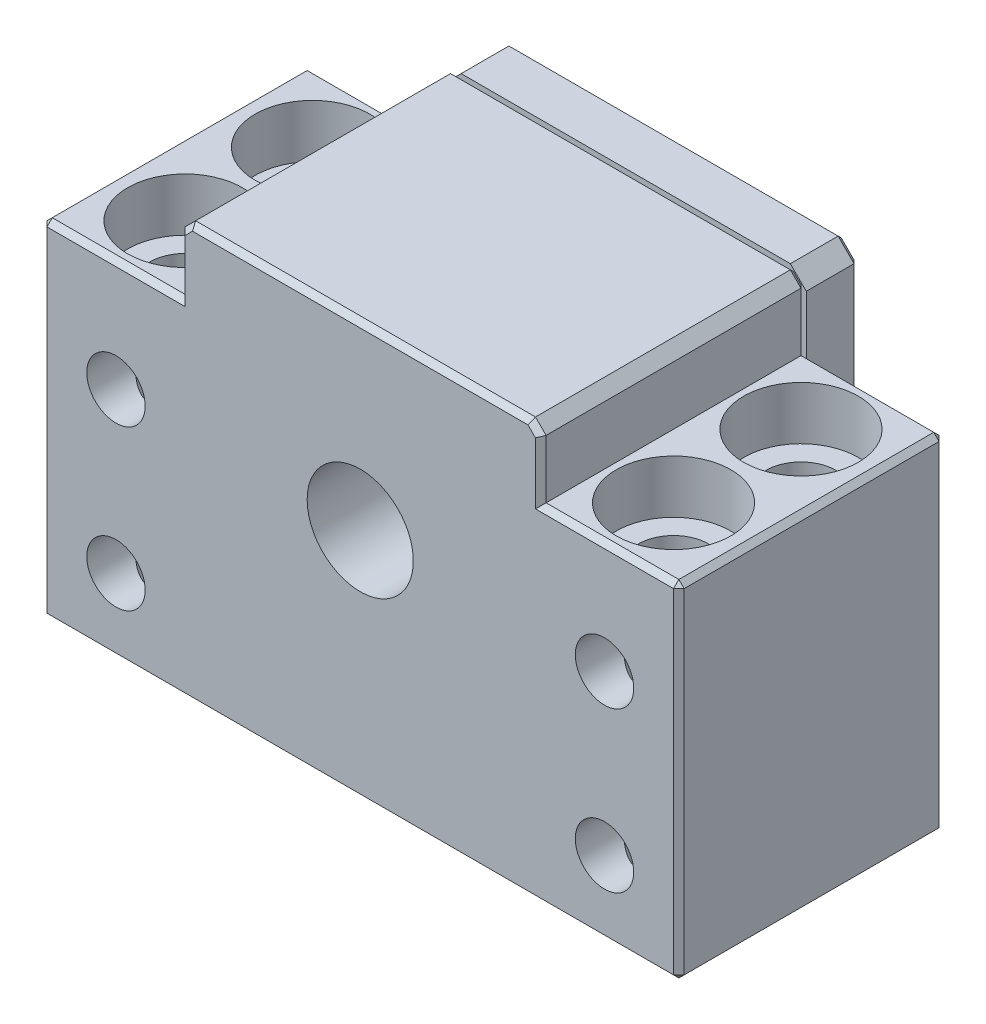
SolidWorks part; units mm, degrees
ref_plane "前视基准面" through (0, 0, 0) normal (0, 0, 1) x (1, 0, 0)
ref_plane "上视基准面" through (0, 0, 0) normal (0, 1, 0) x (1, 0, 0)
ref_plane "右视基准面" through (0, 0, 0) normal (1, 0, 0) x (0, 0, -1)
sketch "草图1" plane through (0, 0, 0) normal (0, 1, 0) x (1, 0, 0)
  line L0 (-23, 12.5) -> (-23, -12.5) construction
  line L1 (-30, 12.5) -> (30, 12.5)
  line L2 (-30, 12.5) -> (-30, -12.5)
  line L3 (-30, -12.5) -> (30, -12.5)
  line L4 (30, 12.5) -> (30, -12.5)
  line L5 (23, 12.5) -> (23, -12.5) construction
  line L6 (-30, -6) -> (30, -6) construction
  line L7 (30, 6) -> (-30, 6) construction
  circle A0 centre (23, 6) radius 3.3
  circle A1 centre (23, -6) radius 3.3
  circle A2 centre (-23, 6) radius 3.3
  circle A3 centre (-23, -6) radius 3.3
  point P0 (0, 0)
  dimension "D1" = 60
  dimension "D2" = 25
  dimension "D3" = 7
  dimension "D4" = 7
  dimension "D5" = 6
  dimension "D6" = 6
extrude "凸台-拉伸1" add sketch "草图1" along normal blind 32.5
sketch "草图2" plane through (0, 32.5, 0) normal (0, 1, 0) x (1, 0, 0)
  circle A0 centre (-23, -6) radius 5.4
  circle A1 centre (-23, 6) radius 5.4
  circle A2 centre (23, -6) radius 5.4
  circle A3 centre (23, 6) radius 5.4
extrude "切除-拉伸1" cut sketch "草图2" against normal blind 5
sketch "草图3" plane through (0, 0, 12.5) normal (0, 0, 1) x (1, 0, 0)
  line L0 (-30, 22) -> (30, 22) construction
  line L1 (-30, 32.5) -> (-30, 0) construction
  line L2 (30, 32.5) -> (30, 0) construction
  line L3 (-30, 7) -> (30, 7) construction
  line L4 (-30, 0) -> (30, 0) construction
  line L5 (23, 0) -> (23, 32.5) construction
  line L6 (-30, 32.5) -> (30, 32.5) construction
  line L7 (-23, 0) -> (-23, 32.5) construction
  circle A0 centre (23, 7) radius 2.75
  circle A1 centre (23, 22) radius 2.75
  circle A2 centre (-23, 22) radius 2.75
  circle A3 centre (-23, 7) radius 2.75
  dimension "D1" = 22
  dimension "D2" = 15
  dimension "D3" = 7
  dimension "D4" = 7
extrude "切除-拉伸2" cut sketch "草图3" against normal through all
ref_plane "基准面1" through (0, 0, -12.5) normal (0, 0, -1) x (-1, 0, 0)
split "分割1" trim tools "基准面1" bodies to split 103 resulting bodies 106
sketch "草图8" plane through (0, 0, -12.5) normal (0, 0, -1) x (-1, 0, 0)
  line L0 (23, 22) -> (-23, 22) construction
  line L2 (17, 39) -> (-17, 39)
  line L3 (17, 39) -> (17, 5)
  line L4 (17, 5) -> (-17, 5)
  line L5 (-17, 39) -> (-17, 5)
  line L6 (17, 39) -> (-17, 5) construction
  line L7 (17, 5) -> (-17, 39) construction
  point P4 (0, 22)
  dimension "D1" = 34
  dimension "D2" = 34
extrude "凸台-拉伸3" add sketch "草图8" along normal blind 5 and the other way through all
sketch "草图9" plane through (0, 0, -17.5) normal (0, 0, -1) x (-1, 0, 0)
  line L0 (17, 22) -> (-17, 22) construction
  line L1 (17, 5) -> (17, 39) construction
  line L2 (-17, 39) -> (-17, 5) construction
  line L3 (17, 39) -> (-17, 5) construction
  line L4 (-17, 5) -> (17, 5) construction
  line L5 (17, 5) -> (-17, 39) construction
  circle A0 centre (0, 22) radius 5
  circle A1 centre (0, 22) radius 17 construction
  circle A2 centre (12.0208, 34.0208) radius 3.5
  circle A3 centre (12.0208, 9.9792) radius 3.5
  circle A4 centre (-12.0208, 9.9792) radius 3.5
  circle A5 centre (-12.0208, 34.0208) radius 3.5
extrude "切除-拉伸6" cut sketch "草图9" against normal blind 5
sketch "草图10" plane through (0, 0, -12.5) normal (0, 0, -1) x (-1, 0, 0)
  circle A0 centre (0, 22) radius 5
extrude "切除-拉伸7" cut sketch "草图10" against normal through all
split "分割2" trim tools "基准面1" bodies to split 113 resulting bodies 114 115
chamfer "倒角1" distance 1.5 angle 45 4 edges at (17, 39, -15) (17, 5, -15) (-17, 5, -15) (-17, 39, -15)
chamfer "倒角2" distance 1 angle 45 2 edges at (-17, 39, 0) (17, 39, 0)
chamfer "倒角3" distance 0.5 angle 45 8 edges at (16.25, 38.25, -17.5) (17, 22, -17.5) (16.25, 5.75, -17.5) (0, 39, -17.5) (-16.25, 38.25, -17.5) (0, 5, -17.5) (-16.25, 5.75, -17.5) (-17, 22, -17.5)
chamfer "倒角4" distance 0.5 angle 45 24 edges at (-23.5, 32.5, -12.5) (0, 0, -12.5) (30, 16.25, -12.5) (-17, 35.25, -12.5) (-16.5, 38.5, -12.5) (0, 39, -12.5) (16.5, 38.5, -12.5) (17, 35.25, -12.5) (23.5, 32.5, -12.5) (16.5, 38.5, 12.5) (17, 35.25, 12.5) (23.5, 32.5, 12.5) (30, 32.5, 0) (30, 16.25, 12.5) (0, 39, 12.5) (-16.5, 38.5, 12.5) (-17, 35.25, 12.5) (-23.5, 32.5, 12.5) (-30, 16.25, -12.5) (-30, 32.5, 0) (-30, 16.25, 12.5) (-30, 0, 0) (0, 0, 12.5) (30, 0, 0)
